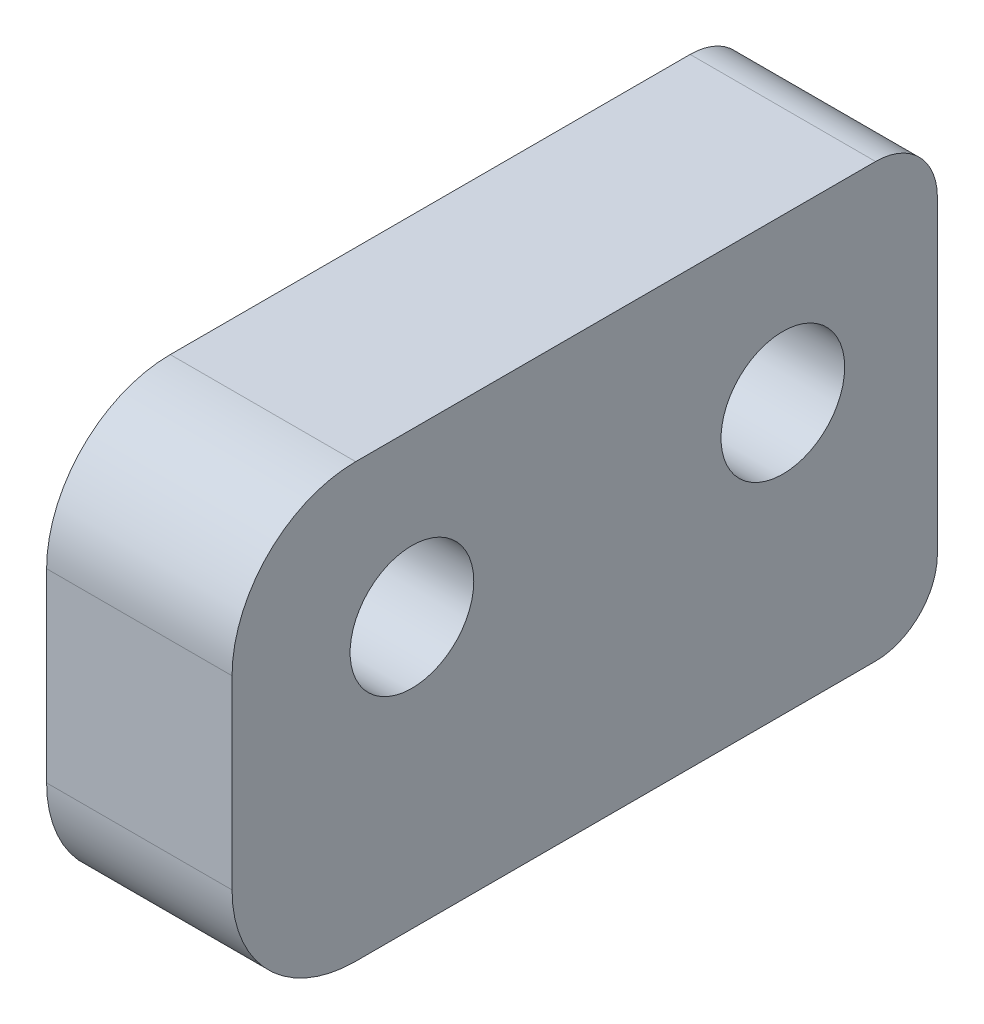
SolidWorks part; units mm, degrees
ref_plane "Front Plane" through (0, 0, 0) normal (0, 0, 1) x (1, 0, 0)
ref_plane "Top Plane" through (0, 0, 0) normal (0, 1, 0) x (1, 0, 0)
ref_plane "Right Plane" through (0, 0, 0) normal (1, 0, 0) x (0, 0, -1)
sketch "Sketch1" plane through (0, 0, 0) normal (1, 0, 0) x (0, 0, -1)
  line L0 (-1.8687, 2.63) -> (2.5, 2.63)
  line L1 (2.5, 2.63) -> (2.5, -4.37)
  line L2 (2.5, -4.37) -> (-8.91, -4.37)
  line L3 (-8.91, -4.37) -> (-8.91, 2.63)
  line L4 (-8.91, 2.63) -> (-1.8687, 2.63)
  circle A0 centre (0, 0) radius 1
  circle A1 centre (-6, 0) radius 1
  point P10 (0, 0)
  point P11 (0, 0)
  point P13 (0.7215, -2.2586)
  point P14 (1.7773, -2.8681)
  dimension "D2" = 2
  dimension "D3" = 2
  dimension "D1" = 6
  dimension "D4" = 2.63
  dimension "D5" = 2.5
  dimension "D6" = 4.37
  dimension "D7" = 2.91
extrude "Boss-Extrude1" add sketch "Sketch1" against normal blind 3
fillet "Fillet1" radius 2 2 edges at (-1.5, -4.37, 8.91) (-1.5, 2.63, 8.91)
fillet "Fillet2" radius 1 2 edges at (-1.5, -4.37, -2.5) (-1.5, 2.63, -2.5)
